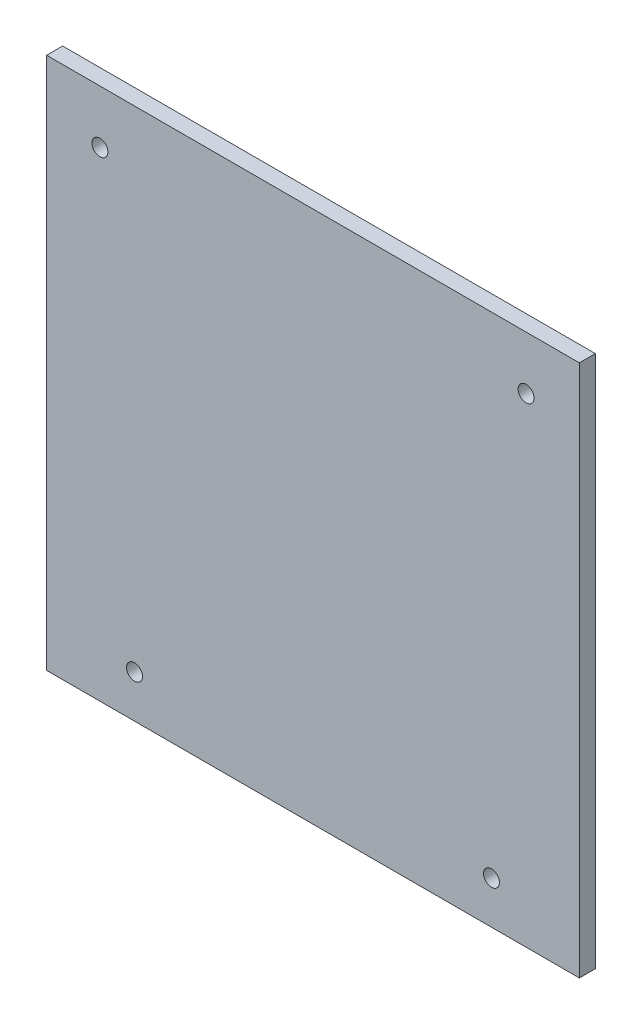
SolidWorks part; units mm, degrees
ref_plane "Front Plane" through (0, 0, 0) normal (0, 0, 1) x (1, 0, 0)
ref_plane "Top Plane" through (0, 0, 0) normal (0, 1, 0) x (1, 0, 0)
ref_plane "Right Plane" through (0, 0, 0) normal (1, 0, 0) x (0, 0, -1)
sketch "Sketch1" plane through (0, 0, 0) normal (0, 0, 1) x (1, 0, 0)
  line L1 (-50, -50) -> (50, -50)
  line L2 (-50, -50) -> (-50, 50)
  line L3 (-50, 50) -> (50, 50)
  line L4 (50, -50) -> (50, 50)
  line L5 (-50, -50) -> (50, 50) construction
  line L6 (-50, 50) -> (50, -50) construction
  point P0 (0, 0)
  dimension "D1" = 100
  dimension "D2" = 100
extrude "Boss-Extrude1" add sketch "Sketch1" along normal blind 3
sketch "Sketch2" plane through (0, 0, 3) normal (0, 0, 1) x (1, 0, 0)
  line L0 (0, 50) -> (0, -50) construction
  line L1 (50, 50) -> (-50, 50) construction
  line L2 (-50, -50) -> (50, -50) construction
  circle A0 centre (-40, 40) radius 1.5
  circle A1 centre (-33.5, -42) radius 1.5
  circle A2 centre (33.5, -42) radius 1.5
  circle A3 centre (40, 40) radius 1.5
  dimension "D1" = 3
  dimension "D4" = 3
  dimension "D2" = 10
  dimension "D3" = 40
  dimension "D5" = 33.5
  dimension "D6" = 8
extrude "Cut-Extrude1" cut sketch "Sketch2" against normal blind 3
